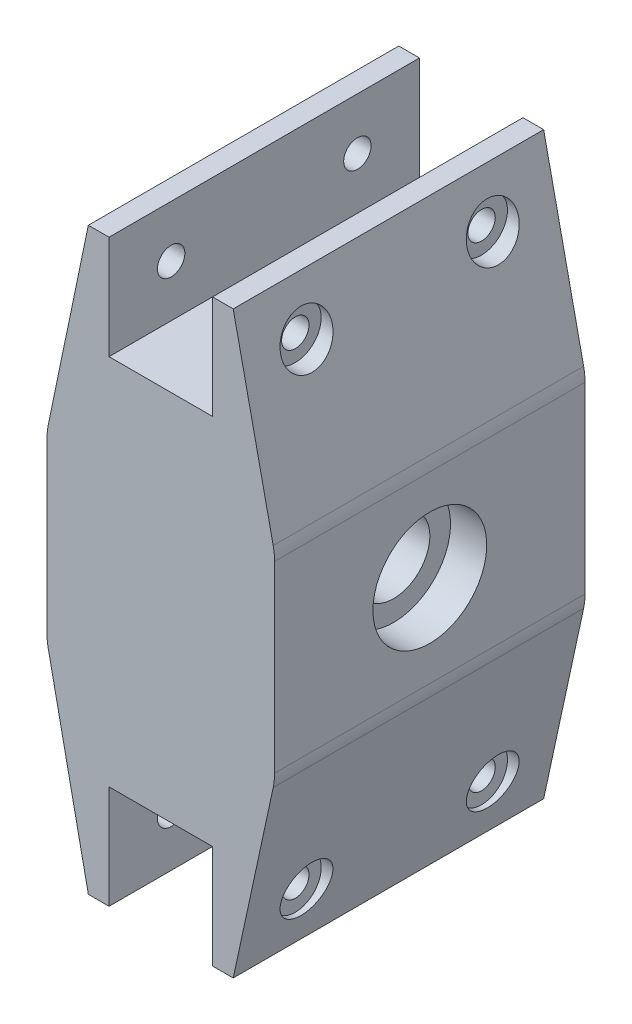
SolidWorks part; units mm, degrees
ref_plane "Front Plane" through (0, 0, 0) normal (0, 0, 1) x (1, 0, 0)
ref_plane "Top Plane" through (0, 0, 0) normal (0, 1, 0) x (1, 0, 0)
ref_plane "Right Plane" through (0, 0, 0) normal (1, 0, 0) x (0, 0, -1)
ref_plane "Plane1" through (0, 0, 60) normal (0, 0, 1) x (1, 0, 0)
sketch "Sketch1" plane through (0, 0, 60) normal (0, 0, 1) x (1, 0, 0)
  line L0 (14, 56) -> (-14, 56)
  line L1 (-14, 56) -> (-22, 17.5)
  line L2 (-22, 17.5) -> (-22, -17.5)
  line L3 (-22, -17.5) -> (-14, -56)
  line L4 (-14, -56) -> (14, -56)
  line L5 (14, -56) -> (22, -19)
  line L6 (22, -19) -> (22, 19)
  line L7 (22, 19) -> (14, 56)
extrude "Boss-Extrude1" add sketch "Sketch1" against normal blind 60
sketch "Sketch2" plane through (0, 0, 0) normal (0, 0, -1) x (-1, 0, 0)
  line L0 (10, 56) -> (-10, 56)
  line L1 (-10, 56) -> (-10, 36)
  line L2 (-10, 36) -> (10, 36)
  line L3 (10, 36) -> (10, 56)
extrude "Cut-Extrude1" cut sketch "Sketch2" against normal through all
sketch "Sketch3" plane through (0, 0, 0) normal (0, 0, -1) x (-1, 0, 0)
  line L0 (-10, -56) -> (10, -56)
  line L1 (10, -56) -> (10, -36)
  line L2 (10, -36) -> (-10, -36)
  line L3 (-10, -36) -> (-10, -56)
extrude "Cut-Extrude2" cut sketch "Sketch3" against normal through all
ref_plane "Plane2" through (0, 0, 30) normal (0, 0, -1) x (-1, 0, 0)
sketch "Sketch4" plane through (0, 0, 30) normal (0, 0, -1) x (-1, 0, 0)
  line L0 (-22, 11) -> (-22, 0)
  line L1 (-22, 0) -> (22, 0)
  line L2 (22, 0) -> (22, 11)
  line L3 (22, 11) -> (15, 11)
  line L4 (15, 11) -> (15, 7)
  line L5 (15, 7) -> (-15, 7)
  line L6 (-15, 7) -> (-15, 11)
  line L7 (-15, 11) -> (-22, 11)
  line L8 (-22, 0) -> (22, 0) construction
revolve "Cut-Revolve1" cut sketch "Sketch4" angle 360 about L8
ref_plane "Plane3" through (17.2432, 0, 0) normal (1, 0, 0) x (0, 0, -1)
hole_wizard "CBORE for M5 Hex Head Bolt1" positions "Sketch6" profile "Sketch5" counterbore size "M5" standard "ANSI Metric"
sketch "Sketch6" plane through (17.2432, 0, 0) normal (1, 0, 0) x (0, 0, -1)
  point P0 (-48, 46)
  point P1 (-12, 46)
  point P2 (-48, -46)
  point P3 (-12, -46)
sketch "Sketch5" plane through (17.2432, 46, 48) normal (0, 1, 0) x (0, 0, -1)
  line L0 (0, 0) -> (0, 7.2432)
  line L1 (0, 7.2432) -> (2.65, 7.2432)
  line L3 (2.65, 7.2432) -> (2.65, 3.2432)
  line L4 (2.65, 3.2432) -> (5, 3.2432)
  line L5 (5, 3.2432) -> (5, 0)
  line L7 (5, 0) -> (0, 0)
  line L11 (0, -6.35) -> (0, 107.95) construction
  dimension "Thru Hole Dia." = 5.3
  dimension "Thru Hole Depth" = 7.2432
  dimension "C'Bore Dia." = 10
  dimension "C'Bore Depth" = 3.2432
ref_plane "Plane4" through (-17.1169, 0, 0) normal (-1, 0, 0) x (0, 0, 1)
hole_wizard "CBORE for M5 Hex Head Bolt2" positions "Sketch8" profile "Sketch7" counterbore size "M5" standard "ANSI Metric"
sketch "Sketch8" plane through (-17.1169, 0, 0) normal (-1, 0, 0) x (0, 0, 1)
  point P0 (48, 46)
  point P1 (12, 46)
  point P2 (48, -46)
  point P3 (12, -46)
sketch "Sketch7" plane through (-17.1169, 46, 48) normal (0, 1, 0) x (0, 0, 1)
  line L0 (0, 0) -> (0, 39.1169)
  line L1 (0, 39.1169) -> (2.65, 39.1169)
  line L3 (2.65, 39.1169) -> (2.65, 3.1169)
  line L4 (2.65, 3.1169) -> (5, 3.1169)
  line L5 (5, 3.1169) -> (5, 0)
  line L7 (5, 0) -> (0, 0)
  line L11 (0, -6.35) -> (0, 107.95) construction
  dimension "Thru Hole Dia." = 5.3
  dimension "Thru Hole Depth" = 39.1169
  dimension "C'Bore Dia." = 10
  dimension "C'Bore Depth" = 3.1169
fillet "Fillet1" radius 12 4 edges at (-22, 17.5, 30) (-22, -17.5, 30) (22, -19, 30) (22, 19, 30)
